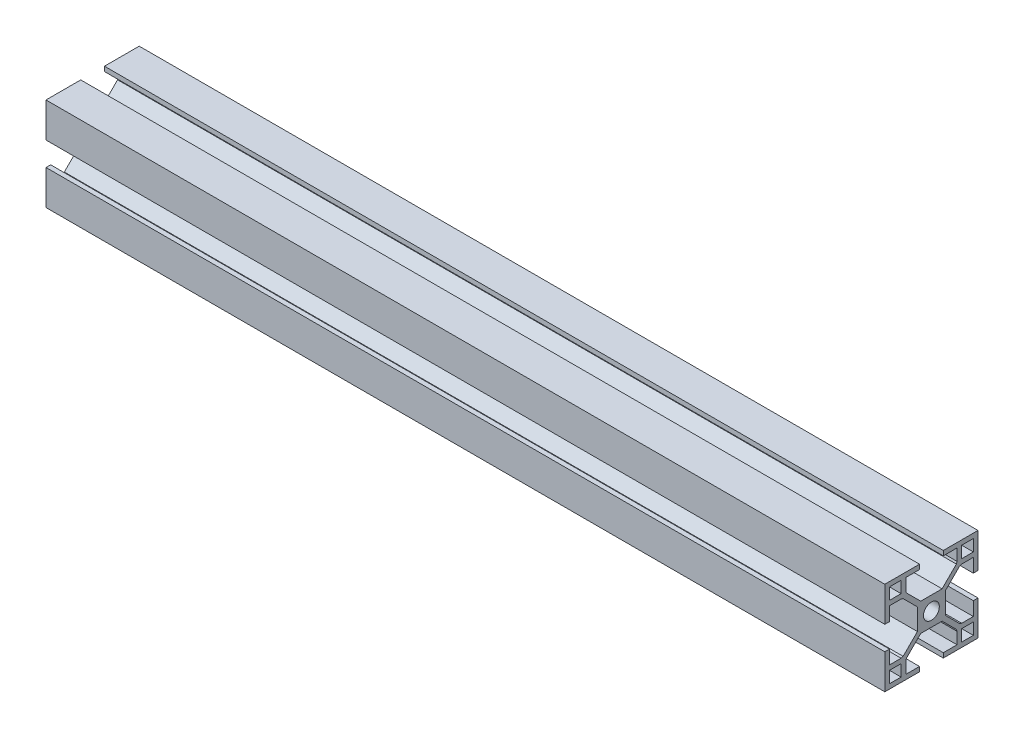
SolidWorks part; units mm, degrees
ref_plane "前视基准面" through (0, 0, 0) normal (0, 0, 1) x (1, 0, 0)
ref_plane "上视基准面" through (0, 0, 0) normal (0, 1, 0) x (1, 0, 0)
ref_plane "右视基准面" through (0, 0, 0) normal (1, 0, 0) x (0, 0, -1)
sketch "草图1" plane through (0, 0, 0) normal (1, 0, 0) x (0, 0, -1)
  line L0 (0, 0) -> (0, 6) construction
  line L5 (0, 6) -> (4.5858, 6)
  line L6 (6, 0) -> (6, -4.5858)
  line L10 (12.133, -10.7188) -> (6, -4.5858)
  line L11 (10.7188, 12.133) -> (4.5858, 6)
  line L12 (20, 20) -> (20, 5.1)
  line L18 (20, -20) -> (5.1, -20)
  line L22 (12.133, -10.7188) -> (13, -11)
  line L23 (18, -13) -> (18, -18)
  line L24 (18, -15.5) -> (18, -13)
  line L28 (18, -13) -> (13, -13)
  line L32 (13, -13) -> (13, -18)
  line L33 (18, -18) -> (13, -18)
  line L34 (11, -13) -> (11, -18)
  line L38 (11, -18) -> (5.1, -18)
  line L42 (10.7188, -12.133) -> (11, -13)
  line L43 (10.7188, -12.133) -> (4.5858, -6)
  line L44 (4.5858, -6) -> (0, -6)
  line L45 (10.7188, 12.133) -> (11, 13)
  line L46 (5.1, -18) -> (5.1, -20)
  line L47 (13, 18) -> (18, 18)
  line L49 (15.5, 18) -> (13, 18)
  line L56 (13, 18) -> (13, 13)
  line L59 (13, 13) -> (18, 13)
  line L60 (18, 18) -> (18, 13)
  line L61 (13, 11) -> (18, 11)
  line L62 (18, 11) -> (18, 5.1)
  line L63 (12.133, 10.7188) -> (13, 11)
  line L64 (12.133, 10.7188) -> (6, 4.5858)
  line L65 (6, 4.5858) -> (6, 0)
  line L66 (18, 5.1) -> (20, 5.1)
  line L67 (11, 18) -> (5.1, 18)
  line L68 (11, 13) -> (11, 18)
  line L69 (5.1, 18) -> (5.1, 20)
  line L70 (20, 20) -> (5.1, 20)
  line L71 (18, -11) -> (18, -5.1)
  line L72 (13, -11) -> (18, -11)
  line L73 (18, -5.1) -> (20, -5.1)
  line L74 (20, -20) -> (20, -5.1)
  line L75 (0, 0) -> (6, 0) construction
  line L76 (0, -6) -> (-4.5858, -6)
  line L77 (-10.7188, -12.133) -> (-4.5858, -6)
  line L78 (-20, -20) -> (-20, -5.1)
  line L79 (-10.7188, -12.133) -> (-11, -13)
  line L80 (-13, -18) -> (-18, -18)
  line L81 (-15.5, -18) -> (-13, -18)
  line L82 (-13, -18) -> (-13, -13)
  line L83 (-13, -13) -> (-18, -13)
  line L84 (-18, -18) -> (-18, -13)
  line L85 (-13, -11) -> (-18, -11)
  line L86 (-18, -11) -> (-18, -5.1)
  line L87 (-12.133, -10.7188) -> (-13, -11)
  line L88 (-12.133, -10.7188) -> (-6, -4.5858)
  line L89 (-6, -4.5858) -> (-6, 0)
  line L90 (-18, -5.1) -> (-20, -5.1)
  line L91 (-11, -18) -> (-5.1, -18)
  line L92 (-11, -13) -> (-11, -18)
  line L93 (-5.1, -18) -> (-5.1, -20)
  line L94 (-20, -20) -> (-5.1, -20)
  line L95 (0, 0) -> (0, -6) construction
  line L96 (-6, 0) -> (-6, 4.5858)
  line L97 (-12.133, 10.7188) -> (-6, 4.5858)
  line L98 (-20, 20) -> (-5.1, 20)
  line L99 (-12.133, 10.7188) -> (-13, 11)
  line L100 (-18, 13) -> (-18, 18)
  line L101 (-18, 15.5) -> (-18, 13)
  line L102 (-18, 13) -> (-13, 13)
  line L103 (-13, 13) -> (-13, 18)
  line L104 (-18, 18) -> (-13, 18)
  line L105 (-11, 13) -> (-11, 18)
  line L106 (-11, 18) -> (-5.1, 18)
  line L107 (-10.7188, 12.133) -> (-11, 13)
  line L108 (-10.7188, 12.133) -> (-4.5858, 6)
  line L109 (-4.5858, 6) -> (0, 6)
  line L110 (-5.1, 18) -> (-5.1, 20)
  line L111 (-18, 11) -> (-18, 5.1)
  line L112 (-13, 11) -> (-18, 11)
  line L113 (-18, 5.1) -> (-20, 5.1)
  line L114 (-20, 20) -> (-20, 5.1)
  line L115 (0, 0) -> (-6, 0) construction
  circle A0 centre (0, 0) radius 3.4
extrude "凸台-拉伸1" add sketch "草图1" along normal blind 360 contours L84 L80 L82 L83 | L33 L23 L28 L32 | L60 L47 L56 L59 | L12 L66 L62 L61 L63 L64 L65 L6 L10 L22 L72 L71 L73 L74 L18 L46 L38 L34 L42 L43 L44 L76 L77 L79 L92 L91 L93 L94 L78 L90 L86 L85 L87 L88 L89 L96 L97 L99 L112 L111 L113 L114 L98 L110 L106 L105 L107 L108 L109 L5 L11 L45 L68 L67 L69 L70 | A0 | L102 L103 L104 L100
